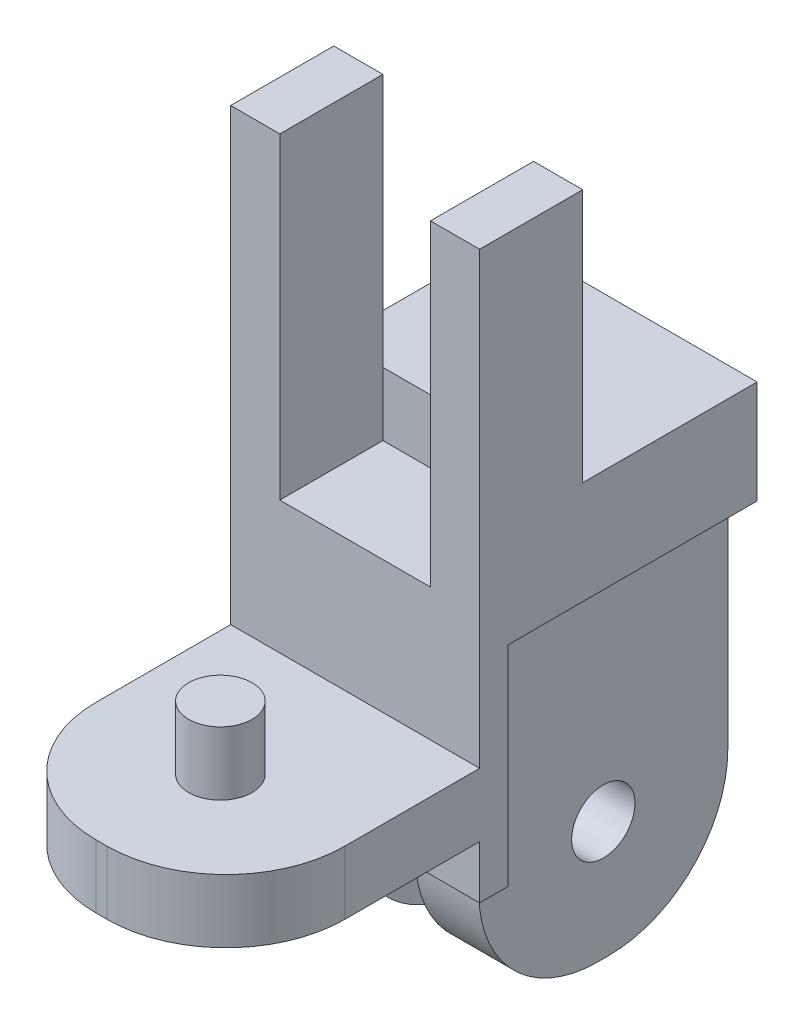
SolidWorks part; units mm, degrees
ref_plane "Front Plane" through (0, 0, 0) normal (0, 0, 1) x (1, 0, 0)
ref_plane "Top Plane" through (0, 0, 0) normal (0, 1, 0) x (1, 0, 0)
ref_plane "Right Plane" through (0, 0, 0) normal (1, 0, 0) x (0, 0, -1)
sketch "Sketch4" plane through (0, 0, 0) normal (0, 0, 1) x (1, 0, 0)
  line L0 (0, 82.063) -> (0, -112.4411) construction
  line L1 (-144.2959, 0) -> (145.5617, 0) construction
  line L2 (-12.7, 12.7) -> (-12.7, -12.7)
  line L3 (-15.7, 15.7) -> (15.7, 15.7)
  line L4 (-15.7, 15.7) -> (-15.7, -15.7)
  line L5 (-15.7, -15.7) -> (15.7, -15.7)
  line L6 (15.7, 15.7) -> (15.7, -15.7)
  line L7 (-12.7, -12.7) -> (12.7, -12.7)
  line L8 (12.7, 12.7) -> (12.7, -12.7)
  line L9 (-12.7, 12.7) -> (12.7, 12.7)
  dimension "D2" = 12.7
  dimension "D3" = 12.7
  dimension "D4" = 12.7
  dimension "D5" = 12.7
  dimension "D1" = 3
extrude "Boss-Extrude3" add sketch "Sketch4" along normal blind 30
sketch "Sketch5" plane through (0, 0, 30) normal (0, 0, 1) x (1, 0, 0)
  line L0 (-15.7, 15.7) -> (15.7, 15.7)
  line L1 (15.7, 15.7) -> (15.7, -15.7)
  line L2 (15.7, -15.7) -> (-15.7, -15.7)
  line L3 (-15.7, -15.7) -> (-15.7, 15.7)
extrude "Boss-Extrude4" add sketch "Sketch5" along normal blind 5
sketch "Sketch6" plane through (0, 0, 35) normal (0, 0, 1) x (1, 0, 0)
  line L0 (-14.6567, 0) -> (15.7, 0) construction
  line L1 (15.7, -15.7) -> (15.7, 15.7) construction
  line L2 (-15.7, 4) -> (15.7, 4)
  line L3 (-15.7, 15.7) -> (-15.7, -15.7) construction
  line L4 (15.7, 4) -> (15.7, -4)
  line L5 (15.7, -4) -> (-15.7, -4)
  line L6 (-15.7, -4) -> (-15.7, 4)
  dimension "D1" = 4
  dimension "D2" = 4
extrude "Boss-Extrude5" add sketch "Sketch6" along normal blind 5
sketch "Sketch7" plane through (0, -4, 0) normal (0, -1, 0) x (1, 0, 0)
  line L0 (-15.7, 40) -> (-15.7, 52)
  line L1 (-0.7, 67) -> (0.7, 67)
  line L2 (15.7, 52) -> (15.7, 40)
  line L3 (-15.7, 40) -> (15.7, 40) construction
  line L4 (15.7, 40) -> (-15.7, 40)
  line L5 (0, 0) -> (0, 92.3619) construction
  arc A0 (0.7, 67) -> (15.7, 52) centre (0.7, 52) cw
  arc A1 (-15.7, 52) -> (-0.7, 67) centre (-0.7, 52) cw
  point P9 (15.7, 67)
  point P12 (-15.7, 67)
  dimension "D3" = 15
  dimension "D1" = 27
  dimension "D2" = 31.4
extrude "Boss-Extrude6" add sketch "Sketch7" against normal blind 8
sketch "Sketch8" plane through (0, -4, 0) normal (0, -1, 0) x (1, 0, 0)
  line L0 (0, 67.4318) -> (0, -5.9603) construction
  line L1 (0.7, 67) -> (-0.7, 67) construction
  circle A0 centre (0, 52) radius 4
  dimension "D1" = 15
extrude "Boss-Extrude7" add sketch "Sketch8" along normal blind 8
mirror "Mirror1" about plane through (0, 0, 0) normal (0, 1, 0) of "Boss-Extrude7"
sketch "Sketch9" plane through (0, 15.7, 0) normal (0, 1, 0) x (1, 0, 0)
  line L1 (-15.7, -32) -> (15.7, -32)
  line L2 (-15.7, -35) -> (-15.7, 0) construction
  line L3 (15.7, -35) -> (15.7, 0) construction
  line L4 (0, 15.8647) -> (0, -78.6922) construction
  line L5 (0, -52) -> (31.7707, -52) construction
  line L6 (31.7707, -52) -> (-30.9902, -52) construction
  line L7 (-15.7, -32) -> (-15.7, -22)
  line L8 (-15.7, -22) -> (15.7, -22)
  line L9 (15.7, -22) -> (15.7, -32)
  dimension "D1" = 20
  dimension "D2" = 10
extrude "Boss-Extrude8" add sketch "Sketch9" along normal blind 5
sketch "Sketch10" plane through (0, 15.7, 0) normal (0, 1, 0) x (1, 0, 0)
  line L0 (-15.7, -22) -> (-15.7, -12)
  line L1 (-15.7, -22) -> (-15.7, 0) construction
  line L2 (-15.7, -12) -> (15.7, -12)
  line L3 (15.7, -22) -> (15.7, 0) construction
  line L4 (15.7, -12) -> (15.7, -22)
  line L5 (15.7, -22) -> (-15.7, -22)
  dimension "D1" = 10
extrude "Boss-Extrude9" add sketch "Sketch10" along normal blind 13
sketch "Sketch11" plane through (0, 20.7, 0) normal (0, 1, 0) x (1, 0, 0)
  line L0 (-15.7, -22) -> (-9.5, -22)
  line L1 (15.7, -22) -> (-15.7, -22) construction
  line L2 (-9.5, -22) -> (-9.5, -32)
  line L3 (-15.7, -32) -> (15.7, -32) construction
  line L4 (-9.5, -32) -> (-15.7, -32)
  line L5 (-15.7, -32) -> (-15.7, -22)
  line L6 (9.5, -22) -> (9.5, -32)
  line L7 (-15.7, -22) -> (15.7, -22) construction
  line L8 (-15.7, -32) -> (15.7, -32) construction
  line L9 (9.5, -32) -> (15.7, -32)
  line L10 (15.7, -32) -> (15.7, -22)
  line L11 (15.7, -32) -> (15.7, -22) construction
  line L12 (15.7, -22) -> (9.5, -22)
  dimension "D1" = 6.2
  dimension "D2" = 6.2
extrude "Boss-Extrude10" add sketch "Sketch11" along normal blind 40
sketch "Sketch12" plane through (0, 0, 32) normal (0, 0, 1) x (1, 0, 0)
  line L0 (-15.7, 60.7) -> (-9.5, 60.7)
  line L1 (-9.5, 60.7) -> (-9.5, 20.7)
  line L2 (-9.5, 20.7) -> (9.5, 20.7)
  line L3 (9.5, 20.7) -> (9.5, 60.7)
  line L4 (9.5, 60.7) -> (15.7, 60.7)
  line L5 (15.7, 60.7) -> (15.7, 15.7)
  line L6 (15.7, 15.7) -> (-15.7, 15.7)
  line L7 (-15.7, 15.7) -> (-15.7, 60.7)
extrude "Boss-Extrude11" add sketch "Sketch12" along normal blind 3
sketch "Sketch13" plane through (-15.7, 0, 0) normal (-1, 0, 0) x (0, 0, 1)
  line L5 (0, 15.7) -> (31.4, 15.7)
  line L6 (31.4, 15.7) -> (31.4, -15.7)
  line L7 (35, -15.7) -> (0, -15.7) construction
  line L8 (31.4, -15.7) -> (0, -15.7)
  line L9 (0, -15.7) -> (0, 15.7)
  dimension "D1" = 31.4
extrude "Cut-Extrude1" cut sketch "Sketch13" against normal blind 31.4
sketch "Sketch15" plane through (0, 0, 12) normal (0, 0, -1) x (-1, 0, 0)
  line L0 (-15.7, 28.7) -> (15.7, 28.7)
  line L1 (15.7, 28.7) -> (15.7, 15.7)
  line L2 (15.7, 15.7) -> (-15.7, 15.7)
  line L3 (-15.7, 15.7) -> (-15.7, 28.7)
extrude "Boss-Extrude12" add sketch "Sketch15" along normal blind 12
sketch "Sketch17" plane through (0, 15.7, 0) normal (0, -1, 0) x (1, 0, 0)
  line L0 (0, 70.9174) -> (0, -6.6676) construction
  line L1 (-12, 31.4) -> (-12, 0)
  line L2 (15.7, 31.4) -> (-15.7, 31.4) construction
  line L3 (15.7, 0) -> (-15.7, 0) construction
  line L4 (-12, 0) -> (-4, 0)
  line L5 (-4, 0) -> (-4, 31.4)
  line L6 (15.7, 31.4) -> (-15.7, 31.4) construction
  line L7 (-4, 31.4) -> (-12, 31.4)
  line L8 (-15.7, 31.4) -> (-15.7, 0) construction
  dimension "D1" = 8
  dimension "D2" = 3.7
  dimension "D3" = 4
extrude "Boss-Extrude13" add sketch "Sketch17" along normal blind 10
sketch "Sketch18" plane through (-12, 0, 0) normal (-1, 0, 0) x (0, 0, 1)
  line L1 (31.4, 5.7) -> (0, 5.7)
  line L4 (0, 5.7) -> (0, -13.3)
  line L5 (15, -28.3) -> (16.4, -28.3)
  line L6 (31.4, -13.3) -> (31.4, 5.7)
  arc A3 (16.4, -28.3) -> (31.4, -13.3) centre (16.4, -13.3) ccw
  arc A4 (0, -13.3) -> (15, -28.3) centre (15, -13.3) ccw
  circle A5 centre (15.7, -13.3) radius 4
  point P12 (0, -28.3)
  dimension "D1" = 34
  dimension "D2" = 15
  dimension "D3" = 15
  dimension "D4" = 15.7
extrude "Boss-Extrude14" add sketch "Sketch18" against normal blind 8
mirror "Mirror3" about plane through (0, 0, 0) normal (1, 0, 0) of "Boss-Extrude13", "Boss-Extrude14"
sketch "Sketch19" plane through (15.7, 0, 0) normal (1, 0, 0) x (0, 0, -1)
  line L0 (-31.4, -10.7) -> (-35, -10.7)
  line L3 (-31.4, -15.7) -> (-31.4, 15.7) construction
  line L4 (-35, -15.7) -> (-35, -4) construction
  line L5 (-35, -10.7) -> (-35, -15.7)
  line L6 (-35, -15.7) -> (-31.4, -15.7)
  line L7 (-31.4, -15.7) -> (-31.4, -10.7)
  dimension "D1" = 5
extrude "Cut-Extrude2" cut sketch "Sketch19" against normal blind 31.4
sketch "Sketch20" plane through (0, -10.7, 0) normal (0, -1, 0) x (1, 0, 0)
  line L0 (-4, 31.4) -> (-4, 32.4)
  line L1 (-4, 32.4) -> (4, 32.4)
  line L2 (4, 32.4) -> (4, 31.4)
  line L3 (4, 31.4) -> (-4, 31.4)
  dimension "D1" = 1
extrude "Cut-Extrude3" cut sketch "Sketch20" against normal blind 26.4
